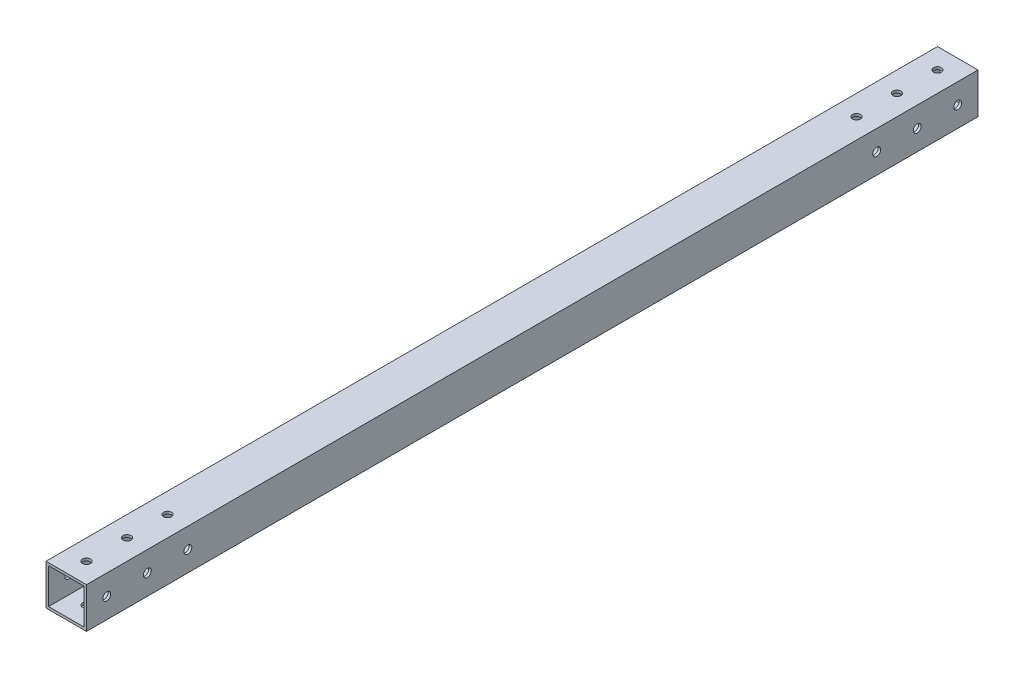
SolidWorks part; units mm, degrees
material "6061-T6 (SS)"
ref_plane "Front Plane" through (0, 0, 0) normal (0, 0, 1) x (1, 0, 0)
ref_plane "Top Plane" through (0, 0, 0) normal (0, 1, 0) x (1, 0, 0)
ref_plane "Right Plane" through (0, 0, 0) normal (1, 0, 0) x (0, 0, -1)
sketch "Sketch1" plane through (0, 0, 0) normal (0, 0, 1) x (1, 0, 0)
  line L1 (0, 0) -> (25.4, 0)
  line L2 (0, 0) -> (0, 25.4)
  line L3 (0, 25.4) -> (25.4, 25.4)
  line L4 (25.4, 0) -> (25.4, 25.4)
  dimension "D1" = 25.4
  dimension "D2" = 25.4
extrude "Boss-Extrude1" add sketch "Sketch1" along normal mid plane 558.8
sketch "Sketch2" plane through (0, 25.4, 0) normal (0, 1, 0) x (1, 0, 0)
  line L0 (25.4, -279.4) -> (0, -279.4) construction
  line L1 (0, -279.4) -> (0, 279.4) construction
  circle A0 centre (12.7, -266.7) radius 2.4892
  circle A1 centre (12.7, -241.3) radius 2.4892
  circle A2 centre (12.7, -215.9) radius 2.4892
  dimension "D1" = 4.9784
  dimension "D2" = 25.4
  dimension "D3" = 25.4
  dimension "D4" = 12.7
  dimension "D5" = 12.7
sketch "Sketch3" plane through (0, 0, 0) normal (-1, 0, 0) x (0, 0, 1)
  line L0 (279.4, 0) -> (-279.4, 0) construction
  line L1 (279.4, 25.4) -> (279.4, 0) construction
  circle A0 centre (266.7, 12.7) radius 2.4892
  circle A1 centre (241.3, 12.7) radius 2.4892
  circle A2 centre (215.9, 12.7) radius 2.4892
  dimension "D1" = 4.9784
  dimension "D2" = 12.7
  dimension "D3" = 12.7
  dimension "D4" = 25.4
  dimension "D5" = 25.4
shell "Shell1" thickness 1.5875
extrude "Cut-Extrude1" cut sketch "Sketch2" against normal through all
extrude "Cut-Extrude2" cut sketch "Sketch3" against normal through all
mirror "Mirror1" about plane through (0, 0, 0) normal (0, 0, 1) of "Cut-Extrude1", "Cut-Extrude2"
